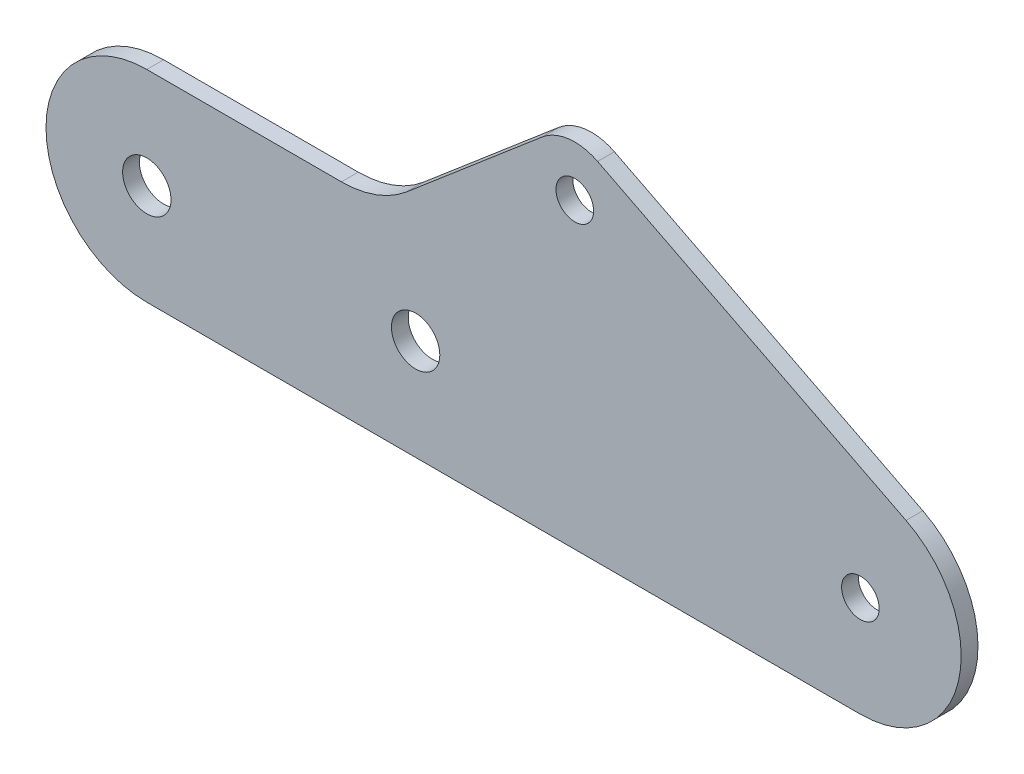
SolidWorks part; units mm, degrees
ref_plane "Front Plane" through (0, 0, 0) normal (0, 0, 1) x (1, 0, 0)
ref_plane "Top Plane" through (0, 0, 0) normal (0, 1, 0) x (1, 0, 0)
ref_plane "Right Plane" through (0, 0, 0) normal (1, 0, 0) x (0, 0, -1)
sketch "Sketch1" plane through (0, 0, 0) normal (0, 0, 1) x (1, 0, 0)
  line L1 (-3.9295, -9.525) -> (38.1, -9.525)
  line L2 (-4.7646, 11.7953) -> (8.0265, 22.6774)
  line L3 (42.4136, 8.4922) -> (13.2693, 23.2961)
  line L4 (-29.3295, 9.525) -> (-10.9366, 9.525)
  line L5 (-29.3295, -9.525) -> (-3.9295, -9.525)
  line L6 (-4.7646, 11.7953) -> (-14.9402, 3.1382) construction
  circle A1 centre (-3.9295, 0) radius 2.286
  circle A2 centre (38.1, 0) radius 1.778
  arc A3 (38.1, -9.525) -> (42.4136, 8.4922) centre (38.1, 0) ccw
  arc A4 (13.2693, 23.2961) -> (8.0265, 22.6774) centre (11.1125, 19.05) ccw
  circle A5 centre (11.1125, 19.05) radius 1.778
  circle A6 centre (-29.3295, 0) radius 2.286
  arc A7 (-29.3295, 9.525) -> (-29.3295, -9.525) centre (-29.3295, 0) ccw
  arc A8 (-10.9366, 9.525) -> (-4.7646, 11.7953) centre (-10.9366, 19.05) ccw
  dimension "D1" = 9.525
  dimension "D2" = 4.572
  dimension "D4" = 19.05
  dimension "D3" = 9.525
  dimension "D7" = 3.556
  dimension "D8" = 19.05
  dimension "D5" = 26.9875
  dimension "D6" = 19.05
  dimension "D9" = 9.525
extrude "Boss-Extrude1" add sketch "Sketch1" along normal blind 1.5875
